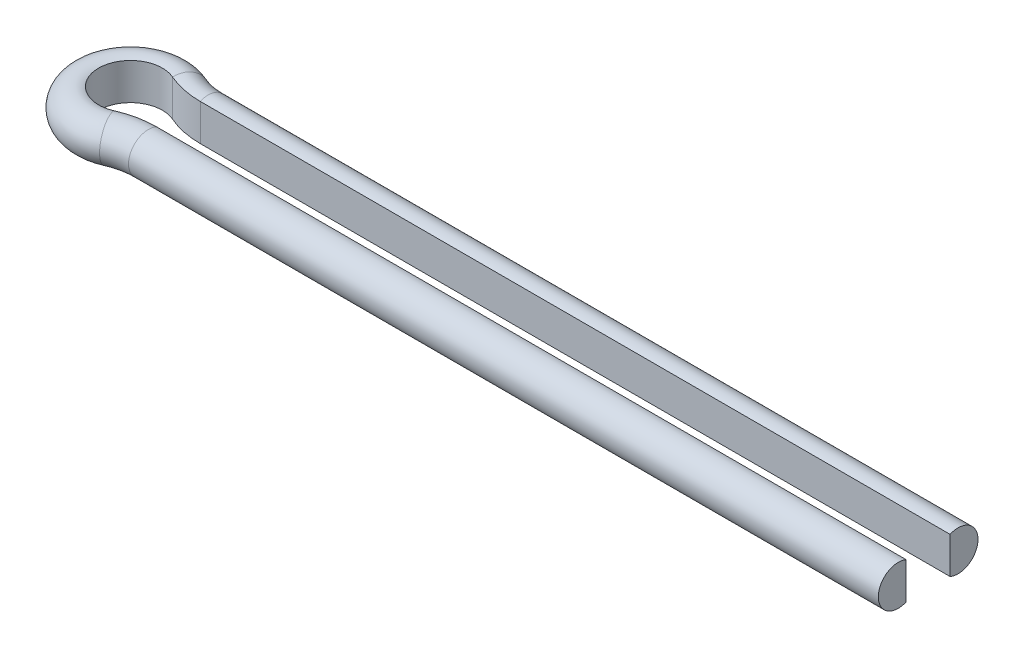
SolidWorks part; units mm, degrees
ref_plane "Front Plane" through (0, 0, 0) normal (0, 0, 1) x (1, 0, 0)
ref_plane "Top Plane" through (0, 0, 0) normal (0, 1, 0) x (1, 0, 0)
ref_plane "Right Plane" through (0, 0, 0) normal (1, 0, 0) x (0, 0, -1)
sketch "Cross-section" plane through (0, 0, 0) normal (1, 0, 0) x (0, 0, -1)
  line L1 (-1, 2.2913) -> (-1, -2.2913)
  arc A1 (-1, -2.2913) -> (-1, 2.2913) centre (0, 0) ccw
  dimension "D1" = 5
  dimension "D2" = 4.5826
sketch "Path" plane through (0, 0, 0) normal (0, 1, 0) x (1, 0, 0)
  line L0 (0, 0) -> (-94.0052, 0)
  line L1 (-94.0052, -7.5) -> (0, -7.5)
  line L2 (0, -2.5) -> (0, 2.5) construction
  arc A0 (-94.0052, 0) -> (-98.0017, 0.8333) centre (-94.0052, 10) cw
  arc A1 (-98.0017, 0.8333) -> (-98.0017, -8.3333) centre (-100, -3.75) ccw
  arc A3 (-98.0017, -8.3333) -> (-94.0052, -7.5) centre (-94.0052, -17.5) cw
  dimension "D3" = 5
  dimension "D4" = 10
  dimension "D5" = 10
  dimension "D1" = 7.5
  dimension "D2" = 100
sweep "Sweep1" add profiles "Cross-section" path "Path"
